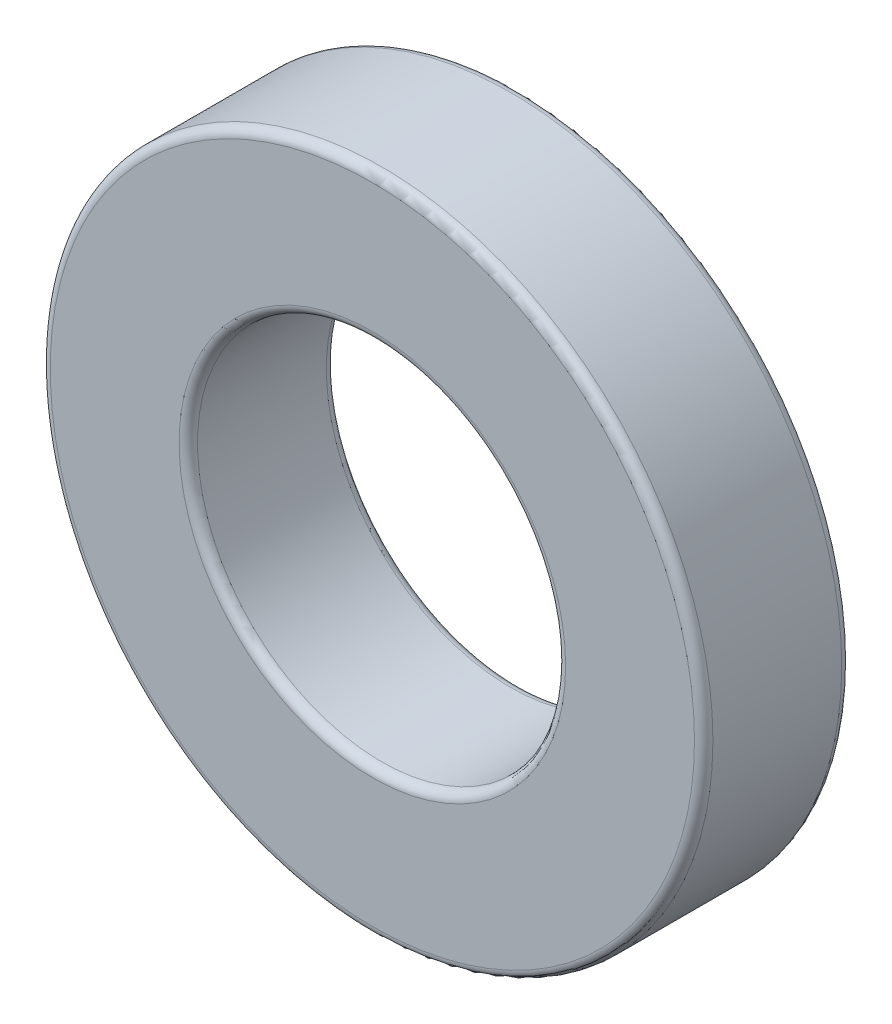
SolidWorks part; units mm, degrees
ref_plane "前视基准面" through (0, 0, 0) normal (0, 0, 1) x (1, 0, 0)
ref_plane "上视基准面" through (0, 0, 0) normal (0, 1, 0) x (1, 0, 0)
ref_plane "右视基准面" through (0, 0, 0) normal (1, 0, 0) x (0, 0, -1)
sketch "草图1" plane through (0, 0, 0) normal (0, 0, 1) x (1, 0, 0)
  circle A0 centre (0, 0) radius 18
  dimension "D1" = 36
extrude "凸台-拉伸1" add sketch "草图1" along normal blind 8
sketch "草图2" plane through (0, 0, 8) normal (0, 0, 1) x (1, 0, 0)
  circle A0 centre (0, 0) radius 10
  dimension "D1" = 20
extrude "切除-拉伸1" cut sketch "草图2" against normal through all
fillet "圆角1" radius 0.5 4 edges at (10, 0, 8) (10, 0, 0) (18, 0, 0) (18, 0, 8)
